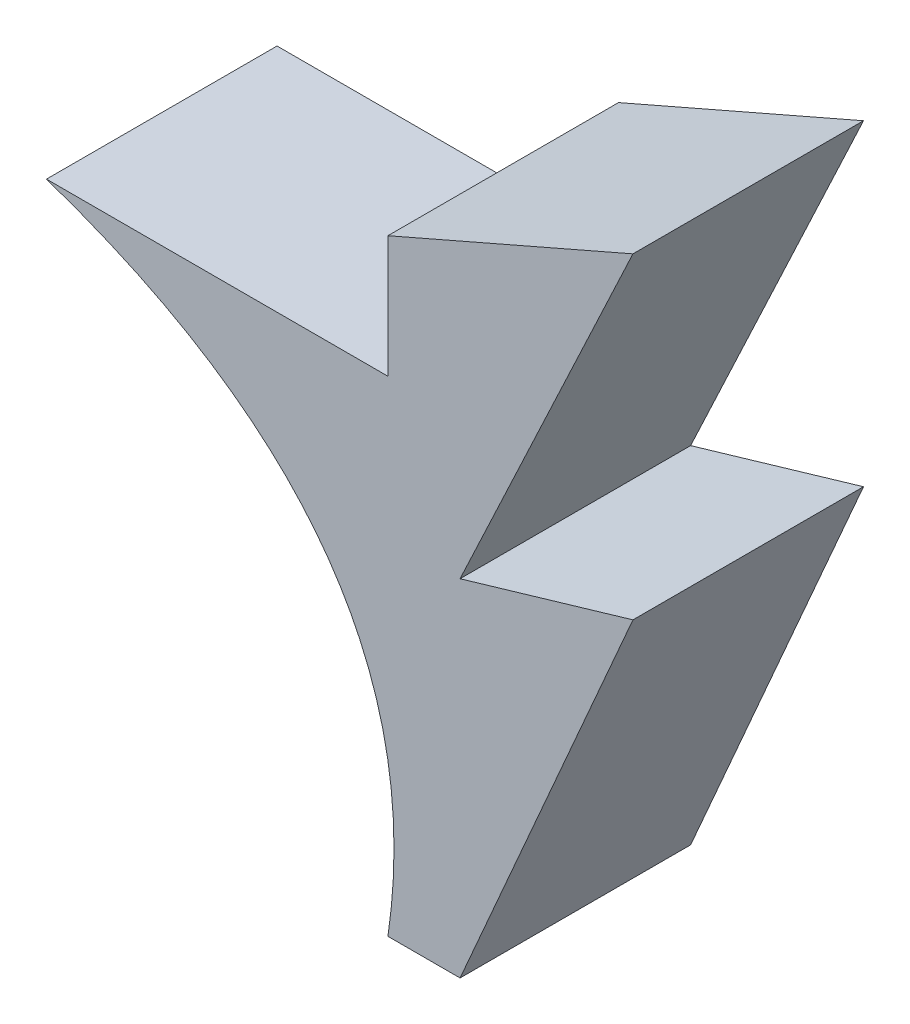
SolidWorks part; units mm, degrees
ref_plane "前基準面" through (0, 0, 0) normal (0, 0, 1) x (1, 0, 0)
ref_plane "上基準面" through (0, 0, 0) normal (0, 1, 0) x (1, 0, 0)
ref_plane "右基準面" through (0, 0, 0) normal (1, 0, 0) x (0, 0, -1)
sketch "草圖1" plane through (0, 0, 0) normal (0, 0, 1) x (1, 0, 0)
  line L0 (-74.0496, 0) -> (0, 0)
  line L1 (0, 0) -> (0, 26.3982)
  line L2 (0, 26.3982) -> (53.1338, 49.5562)
  line L3 (53.1338, 49.5562) -> (15.6405, -30.2092)
  line L4 (15.6405, -30.2092) -> (53.1338, -19.1817)
  line L5 (53.1338, -19.1817) -> (15.6405, -105.1959)
  line L6 (15.6405, -105.1959) -> (0, -105.1959)
  spline S0 degree 2 poles (-74.0496, 0) (11.2841, -28.9262) (0, -105.1959) knots 0 0 0 1 1 1
extrude "填料-伸長1" add sketch "草圖1" along normal blind 50
sketch "草圖2" plane through (0, 0, 0) normal (-1, 0, 0) x (0, 0, 1)
  line L0 (25, 0) -> (25, 26.3982) construction
  line L1 (50, 0) -> (0, 0) construction
  line L2 (50, 26.3982) -> (0, 26.3982) construction
  line L3 (25, 10) -> (25, 26.3982) construction
  line L4 (20, 0) -> (30, 0)
  line L5 (20, 0) -> (20, 10)
  line L6 (20, 10) -> (30, 10)
  line L7 (30, 0) -> (30, 10)
  dimension "D1" = 10
  dimension "D2" = 10
extrude "除料-伸長1" cut sketch "草圖2" against normal blind 10
